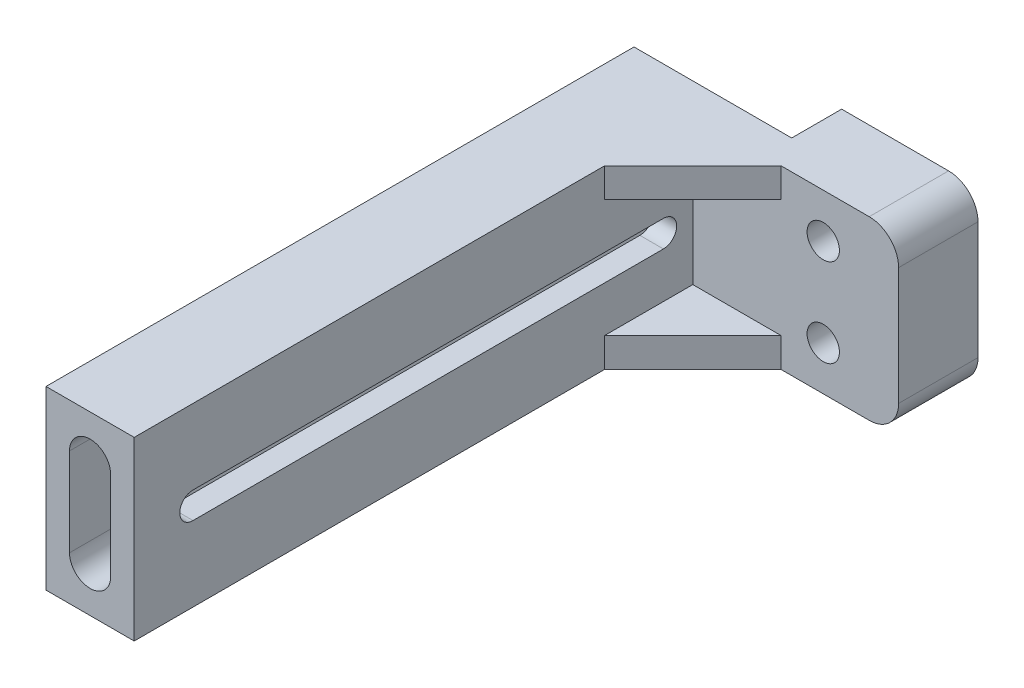
SolidWorks part; units mm, degrees
ref_plane "Front Plane" through (0, 0, 0) normal (0, 0, 1) x (1, 0, 0)
ref_plane "Top Plane" through (0, 0, 0) normal (0, 1, 0) x (1, 0, 0)
ref_plane "Right Plane" through (0, 0, 0) normal (1, 0, 0) x (0, 0, -1)
sketch "Sketch3" plane through (0, 0, 0) normal (0, 0, 1) x (1, 0, 0)
  line L0 (0, 0) -> (0, 15) construction
  line L1 (-3.5, 0) -> (-3.5, 15)
  line L2 (3.5, 0) -> (3.5, 15)
  line L4 (-7.5, -7.5) -> (7.5, -7.5)
  line L5 (-7.5, -7.5) -> (-7.5, 22.5)
  line L6 (-7.5, 22.5) -> (7.5, 22.5)
  line L7 (7.5, -7.5) -> (7.5, 22.5)
  line L8 (-7.5, -7.5) -> (7.5, 22.5) construction
  line L9 (-7.5, 22.5) -> (7.5, -7.5) construction
  arc A0 (-3.5, 0) -> (3.5, 0) centre (0, 0) ccw
  arc A1 (3.5, 15) -> (-3.5, 15) centre (0, 15) ccw
  point P3 (0, 7.5)
  point P8 (0, 7.5)
  dimension "D1" = 7
  dimension "D2" = 30
  dimension "D3" = 15
  dimension "D4" = 15
extrude "Boss-Extrude2" add sketch "Sketch3" along normal blind 100
sketch "Sketch4" plane through (-7.5, 0, 0) normal (-1, 0, 0) x (0, 0, 1)
  line L0 (100, 7.5) -> (0, 7.5) construction
  line L1 (100, 22.5) -> (100, -7.5) construction
  line L2 (0, 22.5) -> (0, -7.5) construction
  line L3 (10, 7.5) -> (90, 7.5) construction
  line L4 (10, 9.75) -> (90, 9.75)
  line L5 (10, 5.25) -> (90, 5.25)
  arc A0 (10, 9.75) -> (10, 5.25) centre (10, 7.5) ccw
  arc A1 (90, 5.25) -> (90, 9.75) centre (90, 7.5) ccw
  point P8 (50, 7.5)
  dimension "D1" = 4.5
  dimension "D2" = 80
extrude "Cut-Extrude1" cut sketch "Sketch4" against normal through all
sketch "Sketch5" plane through (0, 0, 0) normal (0, 0, -1) x (-1, 0, 0)
  line L0 (-7.5, 7.5) -> (-7.5, -7.5)
  line L1 (-7.5, -7.5) -> (-7.5, 22.5) construction
  line L2 (-7.5, -7.5) -> (-7.5, 22.5)
  line L3 (-42.5, 17.5) -> (-42.5, -2.5)
  line L4 (-37.5, -7.5) -> (-14, -7.5)
  line L5 (-14, 22.5) -> (-37.5, 22.5)
  line L7 (-37.5, -7.5) -> (-14, -7.5)
  line L8 (-14, 22.5) -> (-37.5, 22.5)
  line L9 (-7.5, -7.5) -> (-14, -7.5)
  line L10 (-7.5, 22.5) -> (-14, 22.5)
  line L26 (63.2649, -2.5) -> (88, -2.5)
  line L27 (63.2649, -2.5) -> (88, -2.5)
  line L28 (93, 18.5) -> (93, 24.5)
  line L29 (93, 18.5) -> (93, 24.5)
  line L30 (88, 29.5) -> (56.3215, 29.5)
  line L31 (88, 29.5) -> (56.3215, 29.5)
  line L91 (-42.5, 17.5) -> (-42.5, -2.5)
  line L136 (93, 2.5) -> (93, 8.5)
  line L137 (93, 2.5) -> (93, 8.5)
  line L138 (93, 8.5) -> (93, 18.5)
  line L139 (93, 8.5) -> (93, 18.5)
  arc A5 (-9.5882, -10.1471) -> (58.5867, -5.7353) centre (23.5, 7.5) ccw
  arc A8 (-9.5882, -10.1471) -> (58.5867, -5.7353) centre (23.5, 7.5) ccw
  arc A9 (52.4601, 31.3235) -> (-9.5882, 25.1471) centre (23.5, 7.5) ccw
  arc A27 (52.4601, 31.3235) -> (-9.5882, 25.1471) centre (23.5, 7.5) ccw
  arc A50 (88, -2.5) -> (93, 2.5) centre (88, 2.5) ccw
  arc A51 (88, -2.5) -> (93, 2.5) centre (88, 2.5) ccw
  arc A52 (93, 24.5) -> (88, 29.5) centre (88, 24.5) ccw
  arc A53 (93, 24.5) -> (88, 29.5) centre (88, 24.5) ccw
  arc A54 (52.4601, 31.3235) -> (56.3215, 29.5) centre (56.3215, 34.5) ccw
  arc A55 (52.4601, 31.3235) -> (56.3215, 29.5) centre (56.3215, 34.5) ccw
  arc A56 (63.2649, -2.5) -> (58.5867, -5.7353) centre (63.2649, -7.5) ccw
  arc A57 (63.2649, -2.5) -> (58.5867, -5.7353) centre (63.2649, -7.5) ccw
  arc A136 (-37.5, 22.5) -> (-42.5, 17.5) centre (-37.5, 17.5) ccw
  arc A137 (-37.5, 22.5) -> (-42.5, 17.5) centre (-37.5, 17.5) ccw
  arc A138 (-42.5, -2.5) -> (-37.5, -7.5) centre (-37.5, -2.5) ccw
  arc A139 (-42.5, -2.5) -> (-37.5, -7.5) centre (-37.5, -2.5) ccw
  arc A140 (-9.5882, -10.1471) -> (-14, -7.5) centre (-14, -12.5) ccw
  arc A141 (-9.5882, -10.1471) -> (-14, -7.5) centre (-14, -12.5) ccw
  arc A142 (-14, 22.5) -> (-9.5882, 25.1471) centre (-14, 27.5) ccw
  arc A143 (-14, 22.5) -> (-9.5882, 25.1471) centre (-14, 27.5) ccw
  dimension "D1" = 0
extrude "Boss-Extrude3" add sketch "Sketch5" against normal blind 5
sketch "Sketch6" plane through (0, 0, 0) normal (0, 0, -1) x (-1, 0, 0)
  line L4 (7.5, 22.5) -> (-37.5, 22.5)
  line L5 (-42.5, 17.5) -> (-42.5, -2.5)
  line L6 (-37.5, -7.5) -> (7.5, -7.5)
  line L7 (7.5, -7.5) -> (7.5, 22.5)
  line L8 (-8.1228, 22.5) -> (-37.5, 22.5)
  line L10 (-37.5, -7.5) -> (-8.1228, -7.5)
  line L11 (-42.5, 17.5) -> (-42.5, -2.5)
  arc A0 (-8.1228, 22.5) -> (-8.1228, -7.5) centre (23.5, 7.5) ccw
  arc A3 (-37.5, 22.5) -> (-42.5, 17.5) centre (-37.5, 17.5) ccw
  arc A4 (-37.5, 22.5) -> (-42.5, 17.5) centre (-37.5, 17.5) ccw
  arc A7 (-42.5, -2.5) -> (-37.5, -7.5) centre (-37.5, -2.5) ccw
  arc A8 (-42.5, -2.5) -> (-37.5, -7.5) centre (-37.5, -2.5) ccw
  dimension "D1" = 70
  dimension "D2" = 0
extrude "Boss-Extrude4" add sketch "Sketch6" along normal up to surface (8.5 mm away)
fillet "Fillet1" radius 5 2 edges at (8.1228, 22.5, -4.25) (8.1228, -7.5, -4.25)
sketch "Sketch8" plane through (0, 22.5, 0) normal (0, 1, 0) x (1, 0, 0)
  line L1 (7.5, -5) -> (27.5, -5)
  line L2 (7.5, -5) -> (7.5, 8.5)
  line L3 (7.5, 8.5) -> (27.5, 8.5)
  line L4 (27.5, -5) -> (27.5, 8.5)
extrude "Cut-Extrude3" cut sketch "Sketch8" against normal through all
delete or keep bodies "Body-Delete/Keep 1" type delete bodies bodies 108
sketch "Sketch10" plane through (7.5, 0, 0) normal (1, 0, 0) x (0, 0, -1)
  line L0 (-100, 22.5) -> (0, 22.5) construction
  line L1 (0, -7.5) -> (-5, -7.5)
  line L2 (0, -7.5) -> (0, 22.5)
  line L3 (0, 22.5) -> (-5, 22.5)
  line L4 (-5, -7.5) -> (-5, 22.5)
  dimension "D1" = 5
extrude "Boss-Extrude5" add sketch "Sketch10" along normal up to surface (35 mm away)
sketch "Sketch11" plane through (0, 0, 0) normal (0, 0, -1) x (-1, 0, 0)
  line L0 (-42.5, 22.5) -> (7.5, 22.5) construction
  line L1 (-42.5, -7.5) -> (-22.5, -7.5)
  line L2 (-42.5, -7.5) -> (-42.5, 22.5)
  line L3 (-42.5, 22.5) -> (-22.5, 22.5)
  line L5 (-22.5, -7.5) -> (-19.3141, -7.5)
  line L7 (-22.5, 22.5) -> (-19.3141, 22.5)
  arc A1 (-19.3141, 22.5) -> (-19.3141, -7.5) centre (23.5, 7.5) ccw
  circle A2 centre (-29.6829, 0) radius 2.75
  circle A3 centre (-29.6829, 15) radius 2.75
  dimension "D1" = 20
extrude "Boss-Extrude6" add sketch "Sketch11" along normal up to surface (8.5 mm away) contours L1 L5 A1 L7 L3 L2
sketch "Sketch12" plane through (0, 0, -8.5) normal (0, 0, -1) x (-1, 0, 0)
  circle A0 centre (-29.6829, 0) radius 2.75
  circle A1 centre (-29.6829, 15) radius 2.75
extrude "Cut-Extrude4" cut sketch "Sketch12" against normal through all
fillet "Fillet2" radius 5 2 edges at (42.5, 22.5, -1.75) (42.5, -7.5, -1.75)
sketch "Sketch13" plane through (0, -7.5, 0) normal (0, -1, 0) x (1, 0, 0)
  line L0 (7.5, 5) -> (7.5, 20)
  line L1 (7.5, 5) -> (7.5, 100) construction
  line L2 (7.5, 5) -> (22.5, 5)
  line L3 (37.5, 5) -> (7.5, 5) construction
  line L4 (7.5, 20) -> (22.5, 5)
  dimension "D1" = 15
  dimension "D2" = 15
extrude "Boss-Extrude7" add sketch "Sketch13" against normal blind 5
sketch "Sketch14" plane through (0, 22.5, 0) normal (0, 1, 0) x (1, 0, 0)
  line L3 (22.5, -5) -> (7.5, -5)
  line L4 (7.5, -5) -> (7.5, -20)
  line L5 (7.5, -20) -> (22.5, -5)
  line L6 (22.5, -5) -> (7.5, -5)
  line L7 (7.5, -5) -> (7.5, -20)
  line L8 (7.5, -20) -> (22.5, -5)
  dimension "D1" = 0
extrude "Boss-Extrude8" add sketch "Sketch14" against normal blind 5
